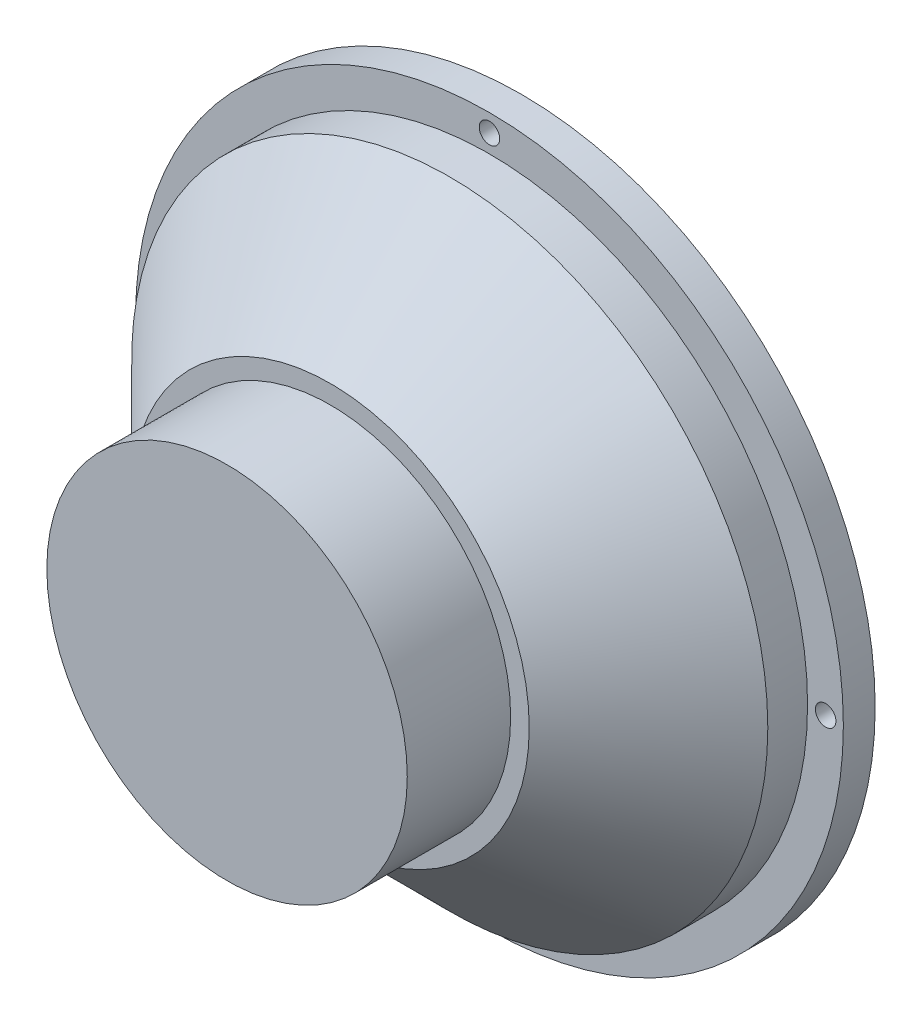
SolidWorks part; units mm, degrees
ref_plane "Front Plane" through (0, 0, 0) normal (0, 0, 1) x (1, 0, 0)
ref_plane "Top Plane" through (0, 0, 0) normal (0, 1, 0) x (1, 0, 0)
ref_plane "Right Plane" through (0, 0, 0) normal (1, 0, 0) x (0, 0, -1)
sketch "Sketch1" plane through (0, 0, 0) normal (0, 0, 1) x (1, 0, 0)
  circle A0 centre (0, 0) radius 89
extrude "Boss-Extrude1" add sketch "Sketch1" along normal blind 8
sketch "Sketch2" plane through (0, 0, 8) normal (0, 0, 1) x (1, 0, 0)
  circle A0 centre (0, 0) radius 80
extrude "Boss-Extrude2" add sketch "Sketch2" along normal blind 40 contours A0
chamfer "Chamfer2" distance 30 angle 45 1 edges at (80, 0, 48)
sketch "Sketch5" plane through (0, 0, 48) normal (0, 0, 1) x (1, 0, 0)
  circle A0 centre (0, 0) radius 45.3253
extrude "Boss-Extrude3" add sketch "Sketch5" along normal blind 26
sketch "Sketch6" plane through (0, 0, 8) normal (0, 0, 1) x (1, 0, 0)
  circle A0 centre (0, 84.548) radius 2.5745
  circle A1 centre (84.548, 0) radius 2.5745
  circle A2 centre (0, -84.548) radius 2.5745
  circle A3 centre (-84.548, 0) radius 2.5745
  point P11 (0, 0)
  dimension "D1" = 4
extrude "Cut-Extrude1" cut sketch "Sketch6" against normal blind 26
